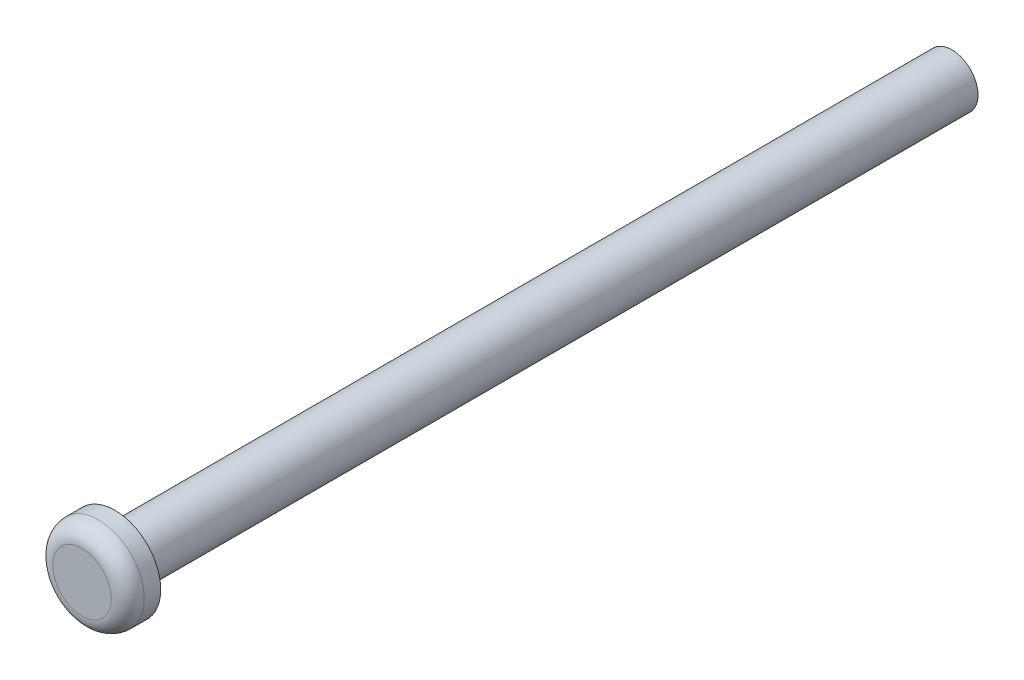
SolidWorks part; units mm, degrees
ref_plane "Front Plane" through (0, 0, 0) normal (0, 0, 1) x (1, 0, 0)
ref_plane "Top Plane" through (0, 0, 0) normal (0, 1, 0) x (1, 0, 0)
ref_plane "Right Plane" through (0, 0, 0) normal (1, 0, 0) x (0, 0, -1)
sketch "Sketch1" plane through (0, 0, 0) normal (0, 0, 1) x (1, 0, 0)
  circle A0 centre (0, 0) radius 3.175
  dimension "D1" = 6.35
extrude "Screwlength" add sketch "Sketch1" against normal blind 101.6
sketch "Sketch2" plane through (0, 0, 0) normal (0, 0, 1) x (1, 0, 0)
  circle A0 centre (0, 0) radius 5.5562
  dimension "D1" = 11.1125
extrude "Head" add sketch "Sketch2" along normal blind 4
fillet "Fillet4" radius 2 1 edges at (5.5562, 0, 4)
